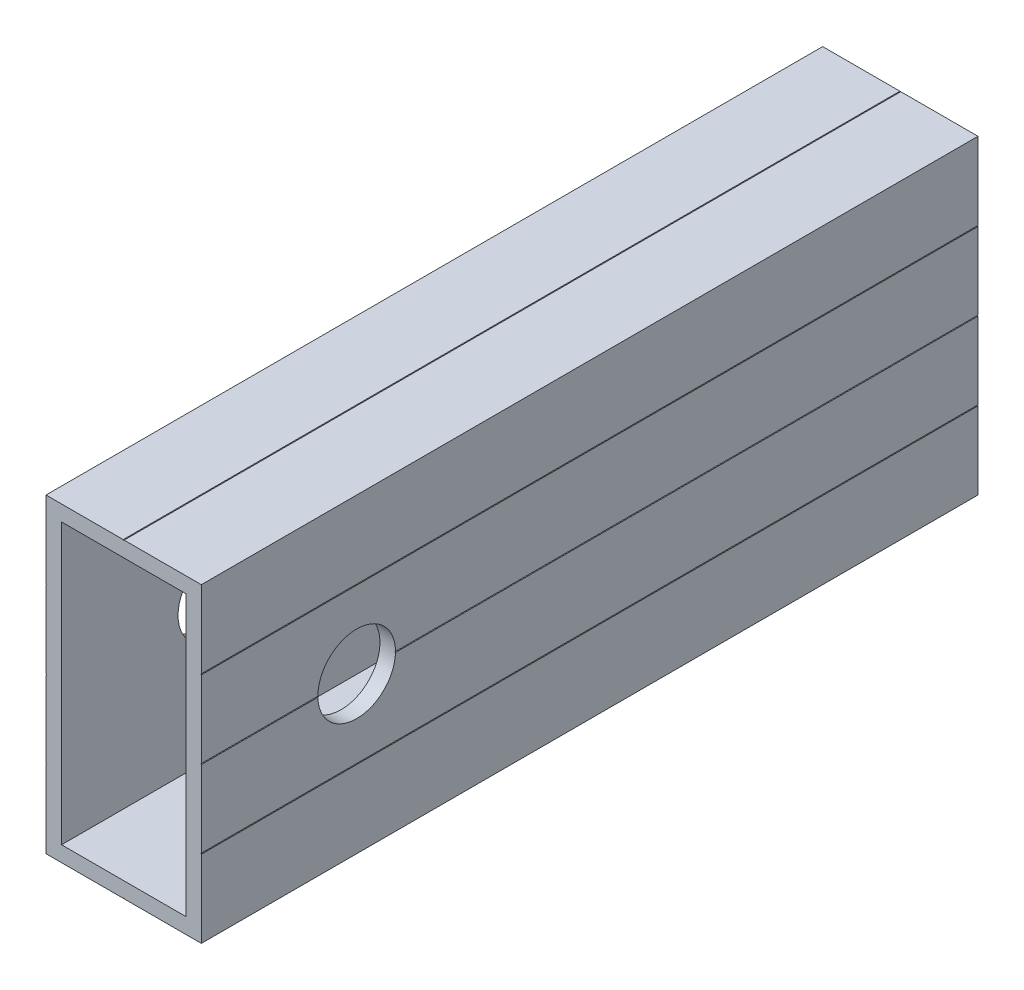
SolidWorks part; units mm, degrees
ref_plane "Front Plane" through (0, 0, 0) normal (0, 0, 1) x (1, 0, 0)
ref_plane "Top Plane" through (0, 0, 0) normal (0, 1, 0) x (1, 0, 0)
ref_plane "Right Plane" through (0, 0, 0) normal (1, 0, 0) x (0, 0, -1)
ref_plane "Plane1" through (12.7, 0, 0) normal (1, 0, 0) x (0, 0, -1)
sketch "Sketch1" plane through (12.7, 0, 0) normal (1, 0, 0) x (0, 0, -1)
  line L0 (-749.3, 25.4) -> (-749.3, -25.4)
  line L1 (-749.3, -25.4) -> (749.3, -25.4)
  line L2 (749.3, -25.4) -> (749.3, 25.4)
  line L3 (749.3, 25.4) -> (-749.3, 25.4)
extrude "Boss-Extrude1" add sketch "Sketch1" against normal blind 25.4
sketch "Sketch2" plane through (0, 0, 749.3) normal (0, 0, 1) x (1, 0, 0)
  line L0 (0.0762, 25.4) -> (-0.0762, 25.4)
  line L1 (-0.0762, 25.4) -> (0.0762, 25.2476)
  line L2 (0.0762, 25.2476) -> (0.0762, 25.4)
extrude "Cut-Extrude1" cut sketch "Sketch2" against normal blind 1498.6
sketch "Sketch3" plane through (0, 0, 749.3) normal (0, 0, 1) x (1, 0, 0)
  line L0 (12.7, 12.6238) -> (12.7, 12.7762)
  line L1 (12.7, 12.7762) -> (12.5476, 12.7762)
  line L2 (12.5476, 12.7762) -> (12.7, 12.6238)
extrude "Cut-Extrude2" cut sketch "Sketch3" against normal through all
sketch "Sketch4" plane through (0, 0, 749.3) normal (0, 0, 1) x (1, 0, 0)
  line L0 (12.7, -0.0762) -> (12.7, 0.0762)
  line L1 (12.7, 0.0762) -> (12.5476, -0.0762)
  line L2 (12.5476, -0.0762) -> (12.7, -0.0762)
extrude "Cut-Extrude3" cut sketch "Sketch4" against normal blind 1498.6
sketch "Sketch5" plane through (0, 0, 749.3) normal (0, 0, 1) x (1, 0, 0)
  line L0 (12.7, -12.7762) -> (12.7, -12.6238)
  line L1 (12.7, -12.6238) -> (12.5476, -12.6238)
  line L2 (12.5476, -12.6238) -> (12.7, -12.7762)
extrude "Cut-Extrude4" cut sketch "Sketch5" against normal blind 1498.6
sketch "Sketch6" plane through (0, 0, 749.3) normal (0, 0, 1) x (1, 0, 0)
  line L0 (0.0762, -25.4) -> (-0.0762, -25.2476)
  line L1 (-0.0762, -25.2476) -> (-0.0762, -25.4)
  line L2 (-0.0762, -25.4) -> (0.0762, -25.4)
extrude "Cut-Extrude5" cut sketch "Sketch6" against normal through all
sketch "Sketch7" plane through (0, 0, 749.3) normal (0, 0, 1) x (1, 0, 0)
  line L0 (-12.7, -12.6238) -> (-12.7, -12.7762)
  line L1 (-12.7, -12.7762) -> (-12.5476, -12.7762)
  line L2 (-12.5476, -12.7762) -> (-12.7, -12.6238)
extrude "Cut-Extrude6" cut sketch "Sketch7" against normal through all
sketch "Sketch8" plane through (0, 0, 749.3) normal (0, 0, 1) x (1, 0, 0)
  line L0 (-12.7, 0.0762) -> (-12.7, -0.0762)
  line L1 (-12.7, -0.0762) -> (-12.5476, 0.0762)
  line L2 (-12.5476, 0.0762) -> (-12.7, 0.0762)
extrude "Cut-Extrude7" cut sketch "Sketch8" against normal blind 1498.6
sketch "Sketch9" plane through (0, 0, 749.3) normal (0, 0, 1) x (1, 0, 0)
  line L0 (-12.7, 12.7762) -> (-12.7, 12.6238)
  line L1 (-12.7, 12.6238) -> (-12.5476, 12.6238)
  line L2 (-12.5476, 12.6238) -> (-12.7, 12.7762)
extrude "Cut-Extrude8" cut sketch "Sketch9" against normal blind 1498.6
sketch "Sketch10" plane through (0, 0, 749.3) normal (0, 0, 1) x (1, 0, 0)
  line L0 (10.16, -22.86) -> (10.16, 22.86)
  line L1 (10.16, 22.86) -> (-10.16, 22.86)
  line L2 (-10.16, 22.86) -> (-10.16, -22.86)
  line L3 (-10.16, -22.86) -> (10.16, -22.86)
extrude "Cut-Extrude9" cut sketch "Sketch10" against normal through all
draft "Draft1" type of draft neutral plane draft angle 45 faces to draft 1 face at (0.0762, 25.3238, 0) neutral plane through (-12.7, 25.4, -749.3) neutral plane normal (0, 1, 0) parameters "D1"=45
draft "Draft2" type of draft neutral plane draft angle 45 faces to draft 1 face at (12.6238, 12.7762, 0) neutral plane through (12.7, 0, 0) neutral plane normal (1, 0, 0) parameters "D1"=45
draft "Draft3" type of draft neutral plane draft angle 45 faces to draft 1 face at (-0.0762, -25.3238, 0) neutral plane through (-12.7, -25.4, 749.3) neutral plane normal (0, -1, 0) parameters "D1"=45
draft "Draft4" type of draft neutral plane draft angle 45 faces to draft 1 face at (-12.6238, -12.7762, 0) neutral plane through (-12.7, 0, 0) neutral plane normal (-1, 0, 0) parameters "D1"=45
draft "Draft5" type of draft neutral plane draft angle 45 faces to draft 2 face at (12.6238, -12.6238, 0) face at (12.6238, 0, 0) neutral plane through (12.7, 0, 0) neutral plane normal (1, 0, 0) parameters "D1"=45
draft "Draft6" type of draft neutral plane draft angle 45 faces to draft 2 face at (-12.6238, 0, 0) face at (-12.6238, 12.6238, 0) neutral plane through (-12.7, 0, 0) neutral plane normal (-1, 0, 0) parameters "D1"=45
sketch "Sketch11" plane through (0, 0, -749.3) normal (0, 0, -1) x (-1, 0, 0)
  line L1 (28.0564, 44.6652) -> (-33.9059, 44.6652)
  line L2 (28.0564, 44.6652) -> (28.0564, -44.0138)
  line L3 (28.0564, -44.0138) -> (-33.9059, -44.0138)
  line L4 (-33.9059, 44.6652) -> (-33.9059, -44.0138)
extrude "Cut-Extrude10" cut sketch "Sketch11" against normal blind 1371.6
sketch "Sketch13" plane through (12.7, 0, 0) normal (1, 0, 0) x (0, 0, -1)
  line L0 (-622.3, 0.0762) -> (-749.3, 0.0762) construction
  line L2 (-749.3, 12.6238) -> (-749.3, 0.0762) construction
  circle A0 centre (-723.9, 0.0762) radius 6.35
  dimension "D1" = 12.7
  dimension "D2" = 25.4
extrude "Cut-Extrude11" cut sketch "Sketch13" against normal blind 25.4
